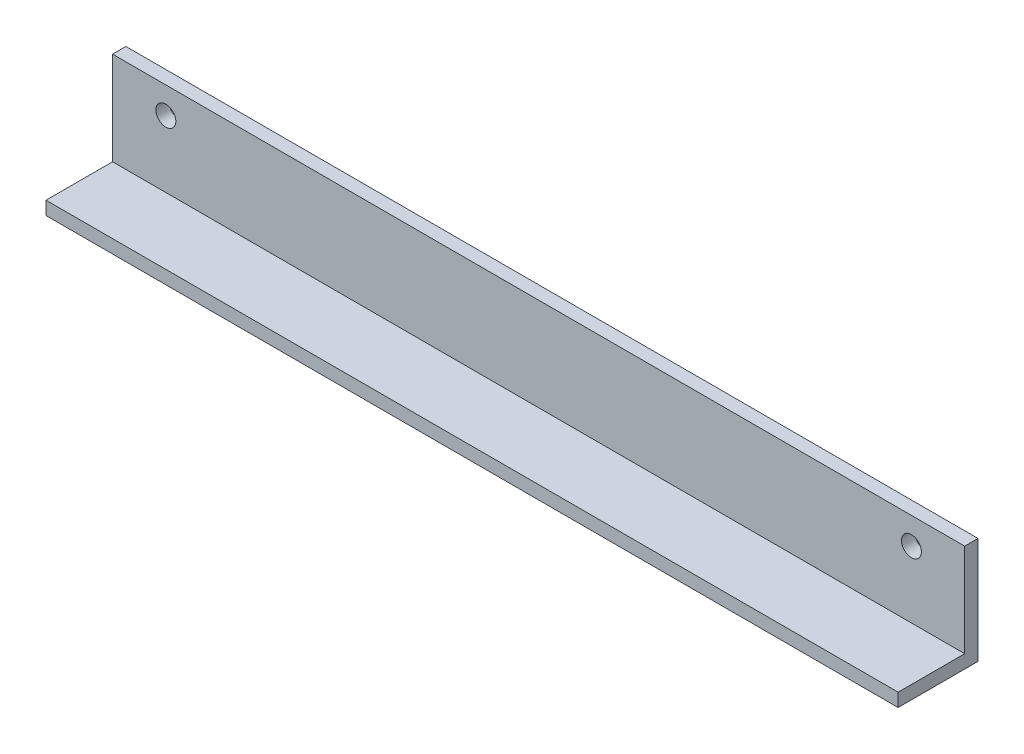
SolidWorks part; units mm, degrees
material "6063-O"
ref_plane "Front Plane" through (0, 0, 0) normal (0, 0, 1) x (1, 0, 0)
ref_plane "Top Plane" through (0, 0, 0) normal (0, 1, 0) x (1, 0, 0)
ref_plane "Right Plane" through (0, 0, 0) normal (1, 0, 0) x (0, 0, -1)
sketch "Sketch1" plane through (0, 0, 0) normal (1, 0, 0) x (0, 0, -1)
  line L0 (-38.1, 0) -> (0, 0)
  line L1 (20.955, 0) -> (-20.955, 0) construction
  line L2 (0, 0) -> (0, 50.8)
  line L3 (0, 20.955) -> (0, -20.955) construction
  dimension "D1" = 50.8
  dimension "D2" = 38.1
extrude "Extrude-Thin1" add sketch "Sketch1" along normal mid plane 406.4 thin thin type one direction reverse wall 6.35
hole_wizard "#10 Clearance Hole1" positions "Sketch2" profile "Sketch3" hole size "#10" standard "ANSI Inch"
sketch "Sketch2" plane through (0, 3.175, 0) normal (0, 1, 0) x (1, 0, 0)
  line L0 (127, -38.1) -> (-127, -38.1) construction
  line L1 (0, -20.955) -> (0, 20.955) construction
  point P0 (-114.3, -15.875)
  point P2 (-114.3, -28.575)
  point P4 (-88.9, -28.575)
  point P6 (-88.9, -15.875)
  point P8 (88.9, -15.875)
  point P10 (88.9, -28.575)
  point P12 (114.3, -28.575)
  point P14 (114.3, -15.875)
  dimension "D1" = 9.525
  dimension "D2" = 12.7
  dimension "D3" = 114.3
  dimension "D4" = 25.4
  dimension "D5" = 114.3
  dimension "D6" = 25.4
sketch "Sketch3" plane through (-114.3, 3.175, 15.875) normal (1, 0, 0) x (0, 0, 1)
  line L0 (0, 0) -> (0, 3.175)
  line L1 (0, 3.175) -> (2.667, 3.175)
  line L2 (2.667, 3.175) -> (2.667, 0)
  line L5 (2.667, 0) -> (0, 0)
  line L11 (0, -6.35) -> (0, 107.95) construction
  dimension "Thru Hole Dia." = 5.334
  dimension "Thru Hole Depth" = 3.175
hole_wizard "3/8 (0.375) Diameter Hole1" positions "Sketch4" profile "Sketch5" hole size "3/8" standard "ANSI Inch" end condition up to next
sketch "Sketch4" plane through (0, 0, 6.35) normal (0, 0, 1) x (1, 0, 0)
  line L0 (203.2, 50.8) -> (-203.2, 50.8) construction
  line L1 (0, -20.955) -> (0, 20.955) construction
  point P0 (-177.8, 38.1)
  point P2 (177.8, 38.1)
  dimension "D1" = 12.7
  dimension "D2" = 355.6
  dimension "D3" = 177.8
sketch "Sketch5" plane through (-177.8, 38.1, 6.35) normal (1, 0, 0) x (0, -1, 0)
  line L0 (0, 0) -> (0, 6.35)
  line L1 (0, 6.35) -> (4.7625, 6.35)
  line L2 (4.7625, 6.35) -> (4.7625, 0)
  line L5 (4.7625, 0) -> (0, 0)
  line L11 (0, -6.35) -> (0, 107.95) construction
  dimension "Thru Hole Dia." = 9.525
  dimension "Thru Hole Depth" = 6.35
